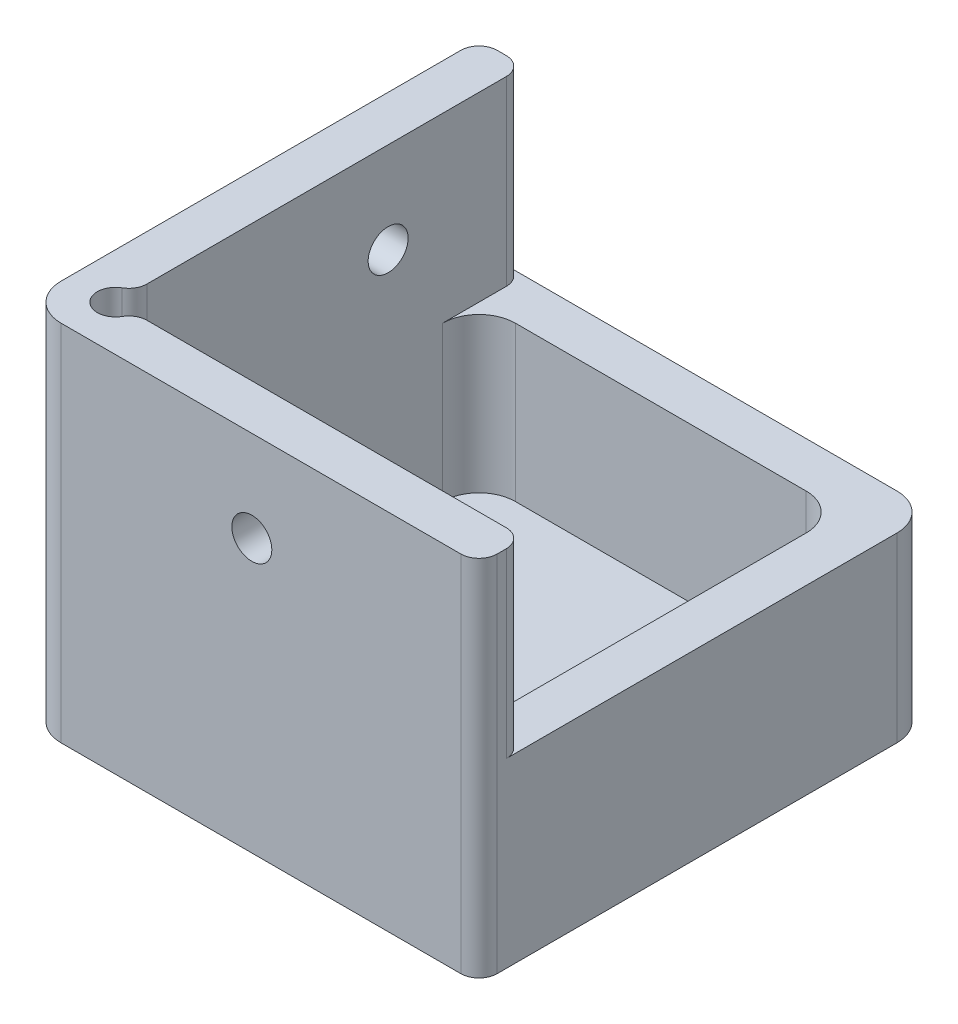
SolidWorks part; units mm, degrees
ref_plane "Front Plane" through (0, 0, 0) normal (0, 0, 1) x (1, 0, 0)
ref_plane "Top Plane" through (0, 0, 0) normal (0, 1, 0) x (1, 0, 0)
ref_plane "Right Plane" through (0, 0, 0) normal (1, 0, 0) x (0, 0, -1)
sketch "ｽｹｯﾁ1" plane through (0, 0, 0) normal (0, 1, 0) x (1, 0, 0)
  line L0 (0, 0) -> (50, 0)
  line L9 (50, 0) -> (50, 5)
  line L10 (50, 5) -> (5, 5)
  line L11 (5, 5) -> (5, 50)
  line L12 (5, 50) -> (0, 50)
  line L13 (0, 50) -> (0, 0)
  dimension "D1" = 5
  dimension "D2" = 50
extrude "ﾎﾞｽ - 押し出し1" add sketch "ｽｹｯﾁ1" along normal blind 20
sketch "ｽｹｯﾁ4" plane through (0, 0, 0) normal (-1, 0, 0) x (0, 0, 1)
  line L1 (-50, 20) -> (-50, 0) construction
  line L3 (0, 20) -> (0, 0) construction
  circle A0 centre (-35, 10) radius 2.2
  point P7 (-50, 10)
  point P10 (0, 0)
  dimension "D1" = 4.4
  dimension "D2" = 35
extrude "ｶｯﾄ - 押し出し2" cut sketch "ｽｹｯﾁ4" against normal up to next
sketch "ｽｹｯﾁ5" plane through (0, 0, 0) normal (0, 0, 1) x (1, 0, 0)
  line L0 (0, 20) -> (50, 20) construction
  line L1 (0, 20) -> (0, 0) construction
  circle A0 centre (25, 10) radius 2.2
  point P4 (25, 20)
  point P7 (0, 10)
  dimension "D1" = 4.4
extrude "ｶｯﾄ - 押し出し3" cut sketch "ｽｹｯﾁ5" against normal up to next
sketch "ｽｹｯﾁ3" plane through (0, 0, 0) normal (0, -1, 0) x (1, 0, 0)
  line L0 (5, -50) -> (0, -50) construction
  line L1 (0, 0) -> (50, 0)
  line L2 (0, 0) -> (0, -50)
  line L3 (0, -50) -> (50, -50)
  line L4 (50, 0) -> (50, -50)
  line L5 (50, 0) -> (50, -5) construction
extrude "ﾎﾞｽ - 押し出し2" add sketch "ｽｹｯﾁ3" along normal blind 20
sketch "ｽｹｯﾁ10" plane through (0, 0, 0) normal (0, 1, 0) x (1, 0, 0)
  line L0 (50, 50) -> (50, 5) construction
  line L1 (5, 5) -> (45, 5)
  line L2 (5, 5) -> (5, 45)
  line L3 (5, 45) -> (45, 45)
  line L4 (45, 5) -> (45, 45)
  dimension "D1" = 5
extrude "ｶｯﾄ - 押し出し5" cut sketch "ｽｹｯﾁ10" against normal offset from surface (17 mm away) 3 up to face at (25, -20, -25)
sketch "ｽｹｯﾁ6" plane through (0, 20, 0) normal (0, 1, 0) x (1, 0, 0)
  circle A0 centre (5, 5) radius 2
  dimension "D1" = 4
extrude "ｶｯﾄ - 押し出し4" cut sketch "ｽｹｯﾁ6" against normal up to surface (37 mm away) up to face at (25, -17, -25)
fillet "ﾌｨﾚｯﾄ1" radius 4 5 edges at (0, 0, 0) (50, -10, -50) (45, -8.5, -45) (45, -8.5, -5) (5, -8.5, -45)
fillet "ﾌｨﾚｯﾄ2" radius 2 6 edges at (5, 10, -50) (0, 0, -50) (50, 0, 0) (50, 10, -5) (5, 1.5, -7) (7, 1.5, -5)
